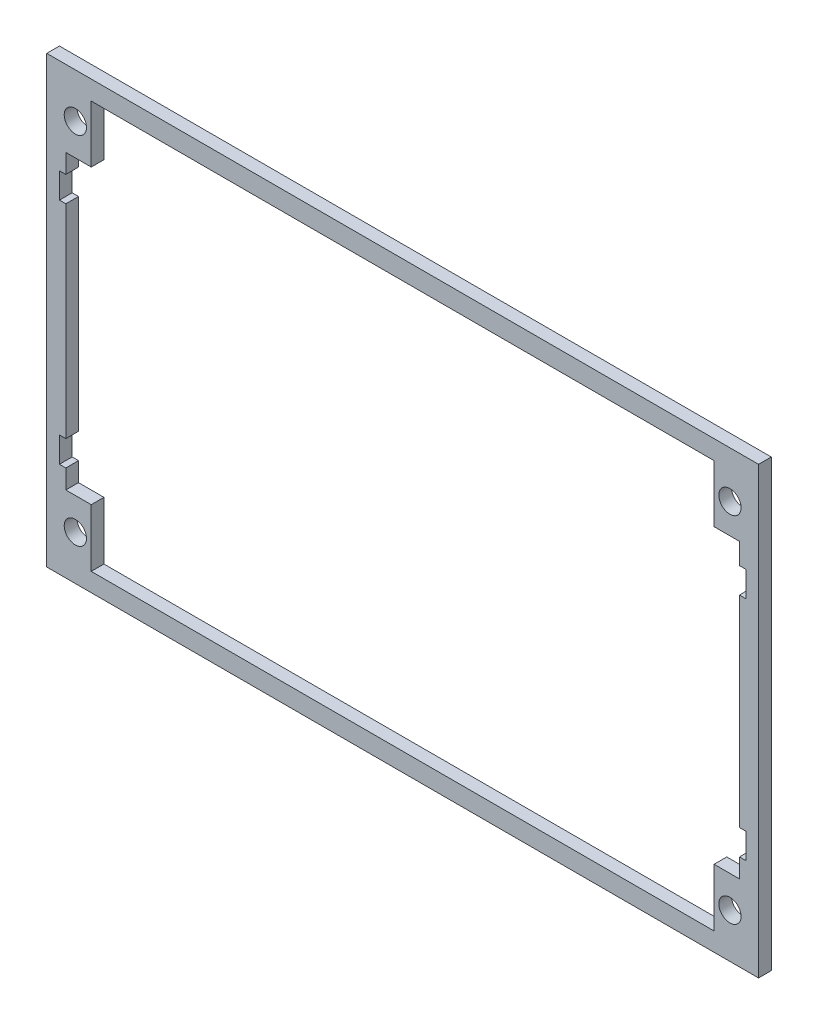
SolidWorks part; units mm, degrees
ref_plane "Ön Düzlem" through (0, 0, 0) normal (0, 0, 1) x (1, 0, 0)
ref_plane "Üst Düzlem" through (0, 0, 0) normal (0, 1, 0) x (1, 0, 0)
ref_plane "Sağ Düzlem" through (0, 0, 0) normal (1, 0, 0) x (0, 0, -1)
sketch "Sketch1" plane through (0, 0, 0) normal (0, 0, 1) x (1, 0, 0)
  line L1 (0, 0) -> (112, 0)
  line L2 (0, 0) -> (0, 70)
  line L3 (0, 70) -> (112, 70)
  line L4 (112, 0) -> (112, 70)
extrude "Boss-Extrude1" add sketch "Sketch1" along normal blind 2
sketch "Sketch2" plane through (0, 0, 2) normal (0, 0, 1) x (1, 0, 0)
  line L0 (0, 70) -> (0, 0) construction
  line L1 (7, 2.9087) -> (105, 2.9087)
  line L2 (7, 2.9087) -> (7, 67)
  line L3 (7, 67) -> (105, 67)
  line L4 (105, 2.9087) -> (105, 67)
  line L5 (112, 70) -> (0, 70) construction
  dimension "D1" = 7
  dimension "D2" = 3
extrude "Cut-Extrude1" cut sketch "Sketch2" against normal through all
sketch "Sketch3" plane through (0, 0, 2) normal (0, 0, 1) x (1, 0, 0)
  line L0 (7, 67) -> (7, 2.9087) construction
  line L1 (3, 12) -> (7, 12)
  line L2 (3, 12) -> (3, 58)
  line L3 (3, 58) -> (7, 58)
  line L4 (7, 12) -> (7, 58)
  line L5 (112, 70) -> (0, 70) construction
  line L6 (0, 70) -> (0, 0) construction
  line L7 (105, 2.9087) -> (105, 67) construction
  line L8 (105, 58) -> (109, 58)
  line L9 (105, 58) -> (105, 12)
  line L10 (105, 12) -> (109, 12)
  line L11 (109, 58) -> (109, 12)
  dimension "D1" = 12
  dimension "D2" = 3
  dimension "D3" = 4
  dimension "D4" = 12
extrude "Cut-Extrude2" cut sketch "Sketch3" against normal through all
sketch "Sketch4" plane through (0, 0, 2) normal (0, 0, 1) x (1, 0, 0)
  line L0 (0, 70) -> (0, 0) construction
  line L1 (112, 70) -> (0, 70) construction
  line L2 (0, 0) -> (112, 0) construction
  line L3 (112, 0) -> (112, 70) construction
  line L4 (3, 58) -> (3, 12) construction
  line L5 (3, 55) -> (2, 55)
  line L6 (3, 55) -> (3, 51)
  line L7 (3, 51) -> (2, 51)
  line L8 (2, 55) -> (2, 51)
  line L9 (109, 12) -> (109, 58) construction
  line L10 (3, 15) -> (2, 15)
  line L11 (3, 15) -> (3, 19)
  line L12 (3, 19) -> (2, 19)
  line L13 (2, 15) -> (2, 19)
  line L14 (109, 54.6898) -> (110, 54.6898)
  line L15 (109, 54.6898) -> (109, 50.6898)
  line L16 (109, 50.6898) -> (110, 50.6898)
  line L17 (110, 54.6898) -> (110, 50.6898)
  line L19 (109, 19) -> (110, 19)
  line L20 (109, 19) -> (109, 15)
  line L21 (109, 15) -> (110, 15)
  line L22 (110, 19) -> (110, 15)
  circle A0 centre (4.5, 63) radius 1.75
  circle A1 centre (4.5, 7) radius 1.75
  circle A2 centre (107.5, 7) radius 1.75
  circle A3 centre (107.5, 62.6898) radius 1.75
  dimension "D1" = 4.5
  dimension "D3" = 7
  dimension "D4" = 4.5
  dimension "D5" = 8
  dimension "D8" = 8
  dimension "D11" = 8
  dimension "D14" = 8
  dimension "D2" = 7
  dimension "D6" = 4
  dimension "D7" = 1
  dimension "D9" = 4
  dimension "D10" = 1
  dimension "D12" = 4
  dimension "D13" = 1
  dimension "D15" = 4
  dimension "D16" = 1
extrude "Cut-Extrude3" cut sketch "Sketch4" against normal through all
